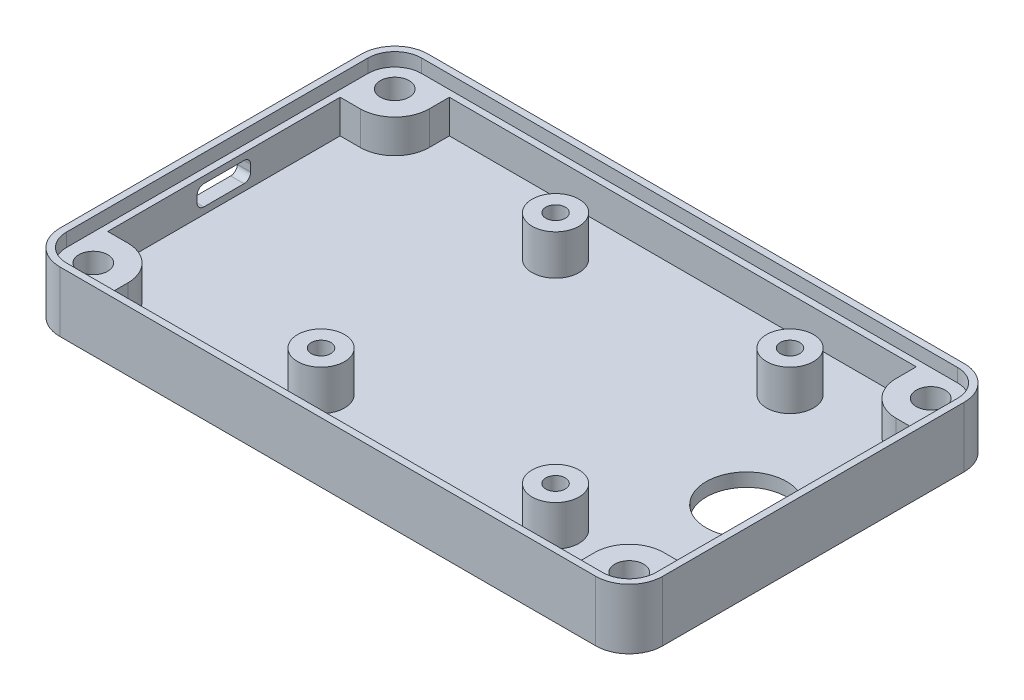
SolidWorks part; units mm, degrees
ref_plane "Plan de face" through (0, 0, 0) normal (0, 0, 1) x (1, 0, 0)
ref_plane "Plan de dessus" through (0, 0, 0) normal (0, 1, 0) x (1, 0, 0)
ref_plane "Plan de droite" through (0, 0, 0) normal (1, 0, 0) x (0, 0, -1)
sketch "Esquisse1" plane through (0, 0, 0) normal (0, 1, 0) x (1, 0, 0)
  line L0 (-33.5, 23.5) -> (33.5, 23.5) construction
  line L1 (-32.5, -22.5) -> (32.5, -22.5) construction
  line L2 (-32.5, -22.5) -> (-32.5, 22.5) construction
  line L3 (-32.5, 22.5) -> (32.5, 22.5) construction
  line L4 (32.5, -22.5) -> (32.5, 22.5) construction
  line L5 (-32.5, -22.5) -> (32.5, 22.5) construction
  line L6 (-32.5, 22.5) -> (32.5, -22.5) construction
  line L7 (33.5, -23.5) -> (33.5, 23.5) construction
  line L8 (-33.5, -23.5) -> (33.5, -23.5) construction
  line L9 (-33.5, -23.5) -> (-33.5, 23.5) construction
  line L11 (-35, -27.5) -> (35, -27.5)
  line L12 (-35, -27.5) -> (-35, 27.5)
  line L13 (-35, 27.5) -> (35, 27.5)
  line L14 (35, -27.5) -> (35, 27.5)
  line L15 (-35, -27.5) -> (35, 27.5) construction
  line L16 (-35, 27.5) -> (35, -27.5) construction
  line L17 (-35, 27.5) -> (-45, 27.5)
  line L18 (-35, 27.5) -> (-35, -27.5)
  line L19 (-35, -27.5) -> (-45, -27.5)
  line L20 (-45, 27.5) -> (-45, -27.5)
  point P0 (0, 0)
  point P10 (0, 0)
  dimension "D1" = 65
  dimension "D2" = 45
  dimension "D4" = 70
  dimension "D5" = 55
  dimension "D6" = 10
  dimension "D3" = 1
extrude "Boss.-Extru.1" add sketch "Esquisse1" along normal blind 2 contours L11 L14 L13 L12 | L17 L20 L19 L12
sketch "Esquisse2" plane through (0, 2, 0) normal (0, 1, 0) x (1, 0, 0)
  circle A0 centre (-11, 17.5) radius 3.5
  circle A1 centre (24, 17.5) radius 3.5
  circle A2 centre (24, -17.5) radius 3.5
  circle A3 centre (-11, -17.5) radius 3.5
  dimension "D5" = 7
  dimension "D1" = 35
  dimension "D2" = 35
  dimension "D3" = 17.5
  dimension "D4" = 11
extrude "Boss.-Extru.2" add sketch "Esquisse2" along normal blind 6
sketch "Esquisse3" plane through (0, 8, 0) normal (0, 1, 0) x (1, 0, 0)
  circle A0 centre (24, 17.5) radius 3.5 construction
  circle A1 centre (-11, -17.5) radius 3.5 construction
  circle A2 centre (24, -17.5) radius 3.5 construction
  circle A3 centre (-11, 17.5) radius 3.5 construction
  circle A4 centre (24, 17.5) radius 3.5 construction
  circle A5 centre (-11, -17.5) radius 3.5 construction
  circle A6 centre (24, -17.5) radius 3.5 construction
  circle A7 centre (-11, 17.5) radius 3.5 construction
  circle A8 centre (-11, 17.5) radius 1.45
  circle A9 centre (24, 17.5) radius 1.45
  circle A10 centre (24, -17.5) radius 1.45
  circle A11 centre (-11, -17.5) radius 1.45
  dimension "D1" = 2.9
extrude "Enlèv. mat.-Extru.1" cut sketch "Esquisse3" against normal blind 4 contours A10 | A11 | A8 | A9
sketch "Esquisse9" plane through (0, 2, 0) normal (0, 1, 0) x (1, 0, 0)
  line L0 (-45, -27.5) -> (35, -27.5) construction
  line L1 (35, 27.5) -> (45, 27.5)
  line L2 (35, 27.5) -> (35, -27.5)
  line L3 (35, -27.5) -> (45, -27.5)
  line L4 (45, 27.5) -> (45, -27.5)
  dimension "D1" = 10
extrude "Boss.-Extru.3" add sketch "Esquisse9" against normal blind 2
sketch "Esquisse10" plane through (0, 2, 0) normal (0, 1, 0) x (1, 0, 0)
  line L0 (45, -27.5) -> (45, 27.5) construction
  circle A0 centre (35, 0) radius 6
  dimension "D1" = 12
  dimension "D2" = 10
extrude "Enlèv. mat.-Extru.8" cut sketch "Esquisse10" against normal blind 2
fillet "Congé2" radius 5 4 edges at (-45, 1, -27.5) (-45, 1, 27.5) (45, 1, 27.5) (45, 1, -27.5)
sketch "Esquisse12" plane through (0, 2, 0) normal (0, 1, 0) x (1, 0, 0)
  line L5 (40, 27.5) -> (-40, 27.5)
  line L7 (40, 27.5) -> (-40, 27.5)
  line L9 (-45, 22.5) -> (-45, -22.5)
  line L13 (45, -22.5) -> (45, 22.5)
  line L16 (45, -22.5) -> (45, 22.5)
  line L18 (-45, 22.5) -> (-45, -22.5)
  line L19 (-40, -27.5) -> (40, -27.5)
  line L20 (-40, -27.5) -> (40, -27.5)
  line L24 (43, -22.5) -> (43, 22.5)
  line L25 (-40, -25.5) -> (40, -25.5)
  line L26 (-43, 22.5) -> (-43, -22.5)
  line L27 (40, 25.5) -> (-40, 25.5)
  line L28 (43, -22.5) -> (43, 22.5)
  line L29 (-40, -25.5) -> (40, -25.5)
  line L30 (-43, 22.5) -> (-43, -22.5)
  line L31 (40, 25.5) -> (-40, 25.5)
  arc A8 (40, -27.5) -> (45, -22.5) centre (40, -22.5) ccw
  arc A9 (40, -27.5) -> (45, -22.5) centre (40, -22.5) ccw
  arc A10 (45, 22.5) -> (40, 27.5) centre (40, 22.5) ccw
  arc A11 (45, 22.5) -> (40, 27.5) centre (40, 22.5) ccw
  arc A16 (-40, 27.5) -> (-45, 22.5) centre (-40, 22.5) ccw
  arc A17 (-40, 27.5) -> (-45, 22.5) centre (-40, 22.5) ccw
  arc A18 (-45, -22.5) -> (-40, -27.5) centre (-40, -22.5) ccw
  arc A19 (-45, -22.5) -> (-40, -27.5) centre (-40, -22.5) ccw
  arc A20 (43, 22.5) -> (40, 25.5) centre (40, 22.5) ccw
  arc A21 (40, -25.5) -> (43, -22.5) centre (40, -22.5) ccw
  arc A22 (-43, -22.5) -> (-40, -25.5) centre (-40, -22.5) ccw
  arc A23 (-40, 25.5) -> (-43, 22.5) centre (-40, 22.5) ccw
  arc A24 (43, 22.5) -> (40, 25.5) centre (40, 22.5) ccw
  arc A25 (40, -25.5) -> (43, -22.5) centre (40, -22.5) ccw
  arc A26 (-43, -22.5) -> (-40, -25.5) centre (-40, -22.5) ccw
  arc A27 (-40, 25.5) -> (-43, 22.5) centre (-40, 22.5) ccw
  dimension "D1" = 2
  dimension "D2" = 0
extrude "Boss.-Extru.4" add sketch "Esquisse12" along normal blind 5
sketch "Esquisse13" plane through (0, 7, 0) normal (0, 1, 0) x (1, 0, 0)
  line L0 (40, 26.5) -> (-40, 26.5)
  line L1 (-44, 22.5) -> (-44, -22.5)
  line L2 (-40, -26.5) -> (40, -26.5)
  line L3 (44, -22.5) -> (44, 22.5)
  line L4 (40, 27.5) -> (-40, 27.5)
  line L5 (-45, 22.5) -> (-45, -22.5)
  line L6 (-40, -27.5) -> (40, -27.5)
  line L7 (45, -22.5) -> (45, 22.5)
  line L8 (40, 27.5) -> (-40, 27.5)
  line L9 (-45, 22.5) -> (-45, -22.5)
  line L10 (-40, -27.5) -> (40, -27.5)
  line L11 (45, -22.5) -> (45, 22.5)
  arc A0 (-40, 26.5) -> (-44, 22.5) centre (-40, 22.5) ccw
  arc A1 (-44, -22.5) -> (-40, -26.5) centre (-40, -22.5) ccw
  arc A2 (40, -26.5) -> (44, -22.5) centre (40, -22.5) ccw
  arc A3 (44, 22.5) -> (40, 26.5) centre (40, 22.5) ccw
  arc A4 (45, 22.5) -> (40, 27.5) centre (40, 22.5) ccw
  arc A5 (-40, 27.5) -> (-45, 22.5) centre (-40, 22.5) ccw
  arc A6 (-45, -22.5) -> (-40, -27.5) centre (-40, -22.5) ccw
  arc A7 (40, -27.5) -> (45, -22.5) centre (40, -22.5) ccw
  arc A8 (45, 22.5) -> (40, 27.5) centre (40, 22.5) ccw
  arc A9 (-40, 27.5) -> (-45, 22.5) centre (-40, 22.5) ccw
  arc A10 (-45, -22.5) -> (-40, -27.5) centre (-40, -22.5) ccw
  arc A11 (40, -27.5) -> (45, -22.5) centre (40, -22.5) ccw
  dimension "D1" = 0
  dimension "D2" = 1
extrude "Boss.-Extru.5" add sketch "Esquisse13" along normal blind 2
sketch "Esquisse15" plane through (0, 2, 0) normal (0, 1, 0) x (1, 0, 0)
  line L0 (-34.85, 22.5) -> (-34.85, 25.5)
  line L1 (-40, 17.35) -> (-43, 17.35)
  line L2 (-34.85, -22.5) -> (-34.85, -25.5)
  line L3 (-40, -17.35) -> (-43, -17.35)
  line L4 (40, 25.5) -> (-40, 25.5)
  line L6 (40, 25.5) -> (-40, 25.5)
  line L12 (-40, -25.5) -> (40, -25.5) construction
  line L13 (34.85, -22.5) -> (34.85, -25.5)
  line L14 (40, -17.35) -> (43, -17.35)
  line L15 (40, 17.35) -> (43, 17.35)
  line L16 (34.85, 22.5) -> (34.85, 25.5)
  line L17 (43, -22.5) -> (43, 22.5) construction
  line L22 (-43, 22.5) -> (-43, -22.5)
  line L24 (-43, 22.5) -> (-43, -22.5)
  line L28 (-40, -25.5) -> (40, -25.5)
  line L29 (-40, -25.5) -> (40, -25.5)
  line L30 (43, -22.5) -> (43, 22.5)
  line L31 (43, -22.5) -> (43, 22.5)
  circle A0 centre (-40, 22.5) radius 2.15
  circle A1 centre (40, 22.5) radius 2.15
  circle A2 centre (40, -22.5) radius 2.15
  circle A3 centre (-40, -22.5) radius 2.15
  arc A12 (-40, 17.35) -> (-34.85, 22.5) centre (-40, 22.5) ccw
  circle A13 centre (-40, 22.5) radius 5.15 construction
  arc A14 (-34.85, -22.5) -> (-40, -17.35) centre (-40, -22.5) ccw
  arc A15 (40, -17.35) -> (34.85, -22.5) centre (40, -22.5) ccw
  arc A16 (34.85, 22.5) -> (40, 17.35) centre (40, 22.5) ccw
  circle A17 centre (40, 22.5) radius 5.15 construction
  circle A18 centre (-40, -22.5) radius 5.15 construction
  circle A19 centre (40, -22.5) radius 5.15 construction
  arc A20 (43, 22.5) -> (40, 25.5) centre (40, 22.5) ccw
  arc A22 (43, 22.5) -> (40, 25.5) centre (40, 22.5) ccw
  arc A26 (-40, 25.5) -> (-43, 22.5) centre (-40, 22.5) ccw
  arc A27 (-40, 25.5) -> (-43, 22.5) centre (-40, 22.5) ccw
  arc A28 (-43, -22.5) -> (-40, -25.5) centre (-40, -22.5) ccw
  arc A29 (-43, -22.5) -> (-40, -25.5) centre (-40, -22.5) ccw
  arc A30 (40, -25.5) -> (43, -22.5) centre (40, -22.5) ccw
  arc A31 (40, -25.5) -> (43, -22.5) centre (40, -22.5) ccw
  dimension "D2" = 4.3
  dimension "D1" = 0
  dimension "D3" = 3
  dimension "D4" = 3
extrude "Boss.-Extru.7" add sketch "Esquisse15" along normal blind 5 contours L1 A12 L0 L6 A27 L24 A0 | L16 A16 L15 L31 A22 L6 A1 | L14 A15 L13 L29 A31 L31 A2 | L2 A14 L3 L24 A29 L29 A3
sketch "Esquisse17" plane through (-45, 0, 0) normal (-1, 0, 0) x (0, 0, 1)
  line L0 (22.5, 0) -> (22.5, 9) construction
  line L1 (-4, 3) -> (4, 3)
  line L2 (-4, 3) -> (-4, 6)
  line L3 (-4, 6) -> (4, 6)
  line L4 (4, 3) -> (4, 6)
  line L5 (-4, 3) -> (4, 6) construction
  line L6 (-4, 6) -> (4, 3) construction
  point P0 (0, 4.5)
  point P5 (0, 0)
  point P9 (22.5, 4.5)
  dimension "D1" = 8
  dimension "D2" = 3
extrude "Enlèv. mat.-Extru.9" cut sketch "Esquisse17" against normal blind 10
fillet "Congé3" radius 1 4 edges at (-44, 3, 4) (-44, 6, 4) (-44, 6, -4) (-44, 3, -4)
